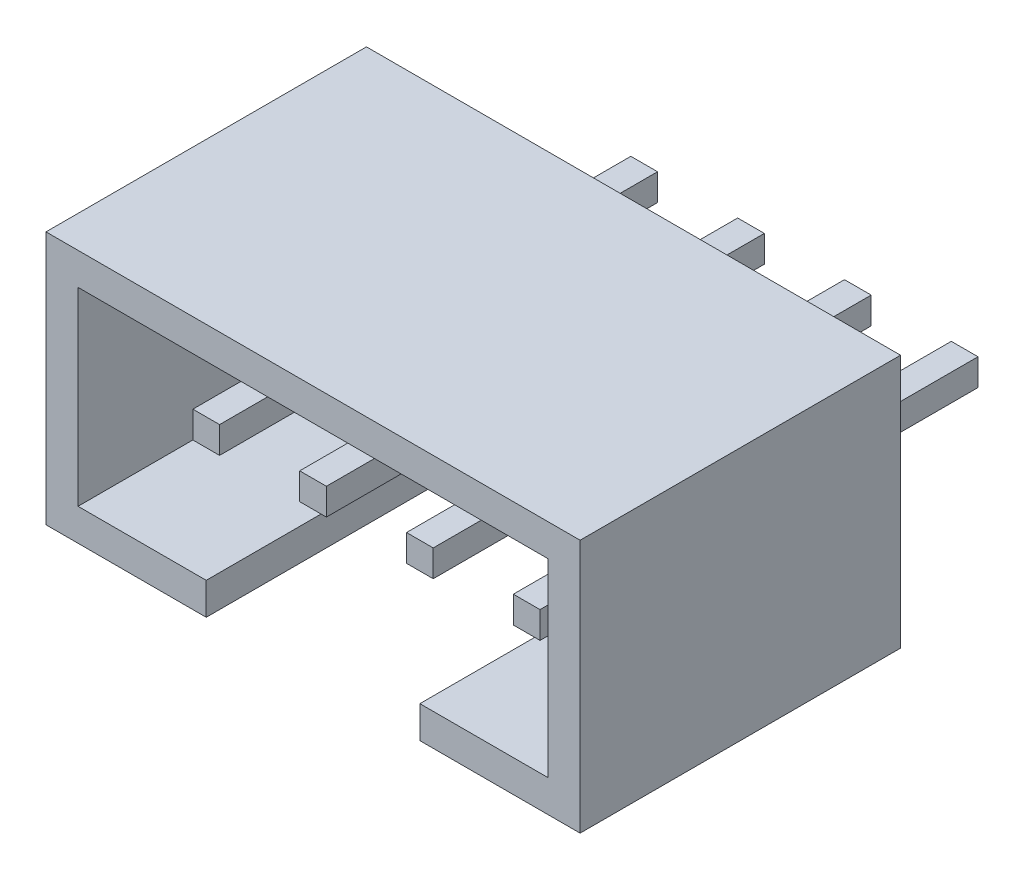
SolidWorks part; units mm, degrees
ref_plane "Front Plane" through (0, 0, 0) normal (0, 0, 1) x (1, 0, 0)
ref_plane "Top Plane" through (0, 0, 0) normal (0, 1, 0) x (1, 0, 0)
ref_plane "Right Plane" through (0, 0, 0) normal (1, 0, 0) x (0, 0, -1)
sketch "Sketch1" plane through (0, 0, 0) normal (0, 0, 1) x (1, 0, 0)
  line L1 (-5, 2.375) -> (5, 2.375)
  line L2 (-5, 2.375) -> (-5, -2.375)
  line L3 (-5, -2.375) -> (5, -2.375)
  line L4 (5, 2.375) -> (5, -2.375)
  line L5 (-5, 2.375) -> (5, -2.375) construction
  line L6 (-5, -2.375) -> (5, 2.375) construction
  point P0 (0, 0)
  dimension "D1" = 10
  dimension "D2" = 4.75
extrude "Boss-Extrude1" add sketch "Sketch1" along normal blind 1.8
sketch "Sketch2" plane through (0, 0, 1.8) normal (0, 0, 1) x (1, 0, 0)
  line L0 (-2, -2.375) -> (-2, -1.775)
  line L1 (-5, -2.375) -> (5, -2.375) construction
  line L2 (-2, -1.775) -> (-4.4, -1.775)
  line L3 (-4.4, -1.775) -> (-4.4, 1.775)
  line L4 (-4.4, 1.775) -> (4.4, 1.775)
  line L5 (0, 1.775) -> (0, 0) construction
  line L6 (-2, -2.375) -> (-5, -2.375)
  line L7 (-5, -2.375) -> (-5, 2.375)
  line L8 (-5, 2.375) -> (5, 2.375)
  line L9 (5, 2.375) -> (-5, 2.375) construction
  line L10 (5, -2.375) -> (5, 2.375)
  line L11 (2, -2.375) -> (5, -2.375)
  line L12 (2, -2.375) -> (2, -1.775)
  line L13 (2, -1.775) -> (4.4, -1.775)
  line L14 (4.4, -1.775) -> (4.4, 1.775)
  point P22 (0, 2.375)
  dimension "D1" = 3
  dimension "D2" = 0.6
  dimension "D3" = 0.6
  dimension "D4" = 0.6
extrude "Boss-Extrude2" add sketch "Sketch2" along normal offset from surface (4.2 mm away) 6 up to face at (0, 0, 0)
sketch "Sketch3" plane through (0, 0, 1.8) normal (0, 0, 1) x (1, 0, 0)
  line L0 (-2, -2.375) -> (2, -2.375) construction
  line L1 (-3.25, -0.125) -> (-2.75, -0.125)
  line L2 (-3.25, -0.125) -> (-3.25, -0.625)
  line L3 (-3.25, -0.625) -> (-2.75, -0.625)
  line L4 (-2.75, -0.125) -> (-2.75, -0.625)
  point P4 (-3.25, -0.375)
  point P7 (-3, -0.625)
  dimension "D1" = 0.5
  dimension "D2" = 2
  dimension "D3" = 3
extrude "Boss-Extrude3" add sketch "Sketch3" along normal offset from surface 5 and the other way blind 5 up to face at (0, 0, 0)
pattern_linear "LPattern1" count 4 spacing 2 along (1, 0, 0) of "Boss-Extrude3"
